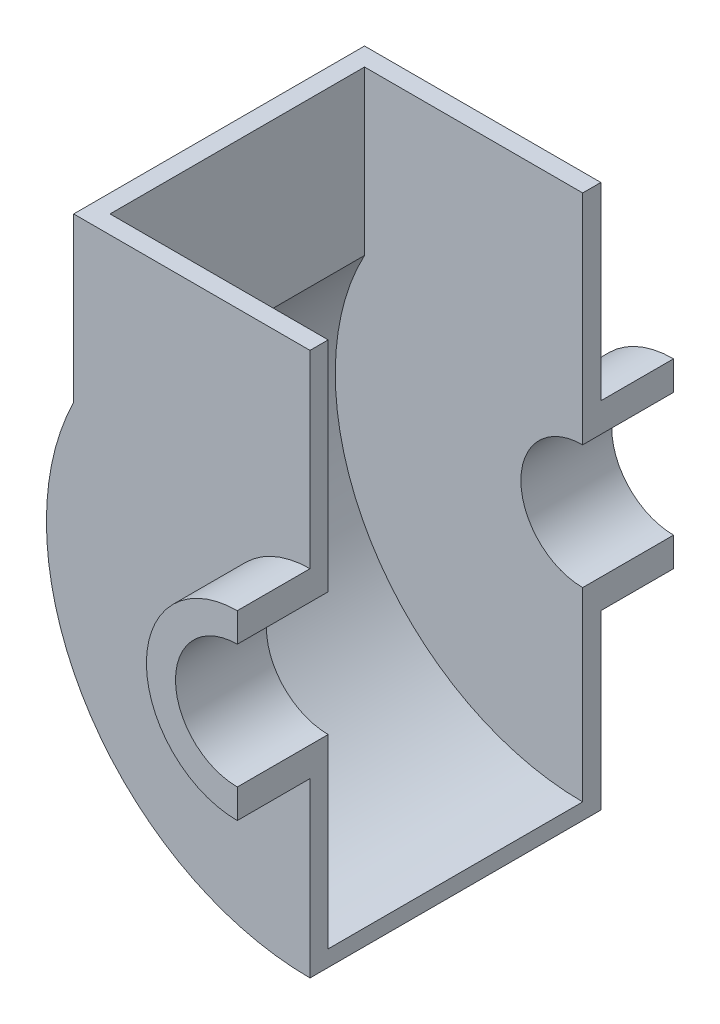
SolidWorks part; units mm, degrees
ref_plane "Front Plane" through (0, 0, 0) normal (0, 0, 1) x (1, 0, 0)
ref_plane "Top Plane" through (0, 0, 0) normal (0, 1, 0) x (1, 0, 0)
ref_plane "Right Plane" through (0, 0, 0) normal (1, 0, 0) x (0, 0, -1)
sketch "Sketch1" plane through (0, 0, 0) normal (0, 0, 1) x (1, 0, 0)
  line L0 (0, 25) -> (0, 17)
  line L1 (0, -17) -> (0, -25)
  arc A0 (0, 25) -> (0, -25) centre (0, 0) ccw
  arc A1 (0, 17) -> (0, -17) centre (0, 0) ccw
  dimension "D1" = 50
  dimension "D2" = 34
extrude "Boss-Extrude1" add sketch "Sketch1" along normal blind 20 and the other way blind 5
sketch "Sketch2" plane through (0, 0, 0) normal (0, 0, 1) x (1, 0, 0)
  line L0 (0, -25) -> (0, -72.5)
  line L1 (0, 25) -> (0, 77)
  line L2 (0, 77) -> (-65, 77)
  line L3 (-65, 77) -> (-65, 32.1131)
  arc A0 (-65, 32.1131) -> (0, -72.5) centre (0, 0) ccw
  arc A1 (0, 25) -> (0, -25) centre (0, 0) ccw
  dimension "D1" = 145
  dimension "D2" = 52
  dimension "D3" = 65
extrude "Boss-Extrude2" add sketch "Sketch2" against normal blind 5 contours A1 L1 L2 L3 A0 L0
ref_plane "Plane1" through (0, 0, -40) normal (0, 0, 1) x (1, 0, 0)
mirror "Mirror3" about plane through (0, 0, -40) normal (0, 0, 1) of bodies 102
sketch "Sketch4" plane through (0, 0, -5) normal (0, 0, -1) x (-1, 0, 0)
  line L0 (65, 32.1131) -> (65, 77)
  line L1 (65, 77) -> (60, 77)
  line L2 (0, 77) -> (65, 77) construction
  line L3 (60, 77) -> (60, 32.1131)
  line L4 (0, -68.0533) -> (0, -72.5)
  arc A0 (0, -72.5) -> (65, 32.1131) centre (0, 0) ccw
  arc A1 (0, -68.0533) -> (60, 32.1131) centre (0, 0) ccw
  dimension "D1" = 5
extrude "Boss-Extrude3" add sketch "Sketch4" along normal up to surface (70 mm away)
